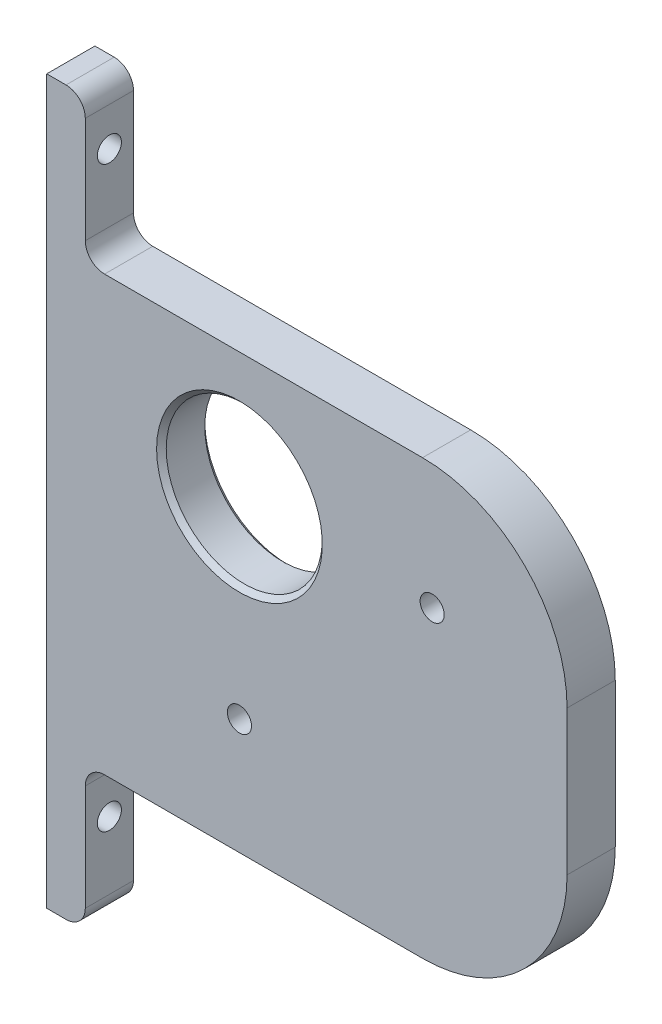
SolidWorks part; units mm, degrees
material "6063-T5"
ref_plane "前视基准面" through (0, 0, 0) normal (0, 0, 1) x (1, 0, 0)
ref_plane "上视基准面" through (0, 0, 0) normal (0, 1, 0) x (1, 0, 0)
ref_plane "右视基准面" through (0, 0, 0) normal (1, 0, 0) x (0, 0, -1)
sketch "草图1" plane through (0, 0, 0) normal (0, 0, 1) x (1, 0, 0)
  line L0 (4, 60) -> (4, 75)
  line L1 (0, 0) -> (4, 0)
  line L2 (0, 0) -> (0, 75)
  line L3 (0, 75) -> (4, 75)
  line L4 (4, 0) -> (4, 15)
  line L5 (4, 60) -> (70, 60)
  line L7 (4, 15) -> (70, 15)
  line L8 (70, 60) -> (70, 15)
  line L9 (60, 52.5) -> (60, 22.5) construction
  circle A0 centre (60, 52.5) radius 2.1 construction
  circle A1 centre (60, 22.5) radius 1.9862 construction
  circle A2 centre (20, 47) radius 8.1
  point P9 (0, 37.5)
  point P10 (70, 37.5)
  point P17 (60, 37.5)
  dimension "D5" = 28
  dimension "D6" = 20
  dimension "D7" = 16.2
  dimension "D8" = 4.2
  dimension "D9" = 30
  dimension "D10" = 10
  dimension "D1" = 4
  dimension "D2" = 75
  dimension "D3" = 45
  dimension "D4" = 70
extrude "凸台-拉伸1" add sketch "草图1" along normal blind 5
sketch "草图2" plane through (4, 0, 0) normal (1, 0, 0) x (0, 0, -1)
  line L0 (-5, 37.5) -> (0, 37.5) construction
  line L1 (-5, 15) -> (-5, 60) construction
  line L2 (0, 15) -> (0, 60) construction
  line L3 (-5, 75) -> (0, 75) construction
  line L5 (-5, 0) -> (0, 0) construction
  circle A0 centre (-2.5, 69) radius 1.25
  circle A1 centre (-2.5, 9) radius 1.25
  point P11 (-2.5, 37.5)
  dimension "D1" = 2.5
  dimension "D2" = 6
  dimension "D4" = 2.5
  dimension "D3" = 9
extrude "切除-拉伸1" cut sketch "草图2" against normal blind 5
sketch "草图3" plane through (0, 0, 0) normal (0, 0, -1) x (-1, 0, 0)
  line L0 (-70, 60) -> (-4, 60) construction
  circle A0 centre (-20, 47) radius 20 construction
  circle A1 centre (-40, 47) radius 1.25
  circle A2 centre (-20, 27) radius 1.25
  dimension "D1" = 40
  dimension "D2" = 2.5
  dimension "D3" = 13
extrude "切除-拉伸2" cut sketch "草图3" against normal blind 120
chamfer "倒角1" distance 0.5 angle 45 2 edges at (28.1, 47, 5) (28.1, 47, 0)
sketch "草图4" plane through (0, 0, 0) normal (0, 0, -1) x (-1, 0, 0)
  line L1 (-4, 15) -> (-70, 15) construction
  line L2 (-70, 60) -> (-54, 60)
  line L3 (-70, 60) -> (-70, 15)
  line L4 (-70, 15) -> (-54, 15)
  line L5 (-54, 60) -> (-54, 15)
  dimension "D1" = 16
extrude "切除-拉伸3" cut sketch "草图4" against normal blind 10
fillet "圆角1" radius 2 4 edges at (4, 15, 2.5) (4, 60, 2.5) (4, 0, 2.5) (4, 75, 2.5)
fillet "圆角2" radius 15 2 edges at (54, 15, 2.5) (54, 60, 2.5)
